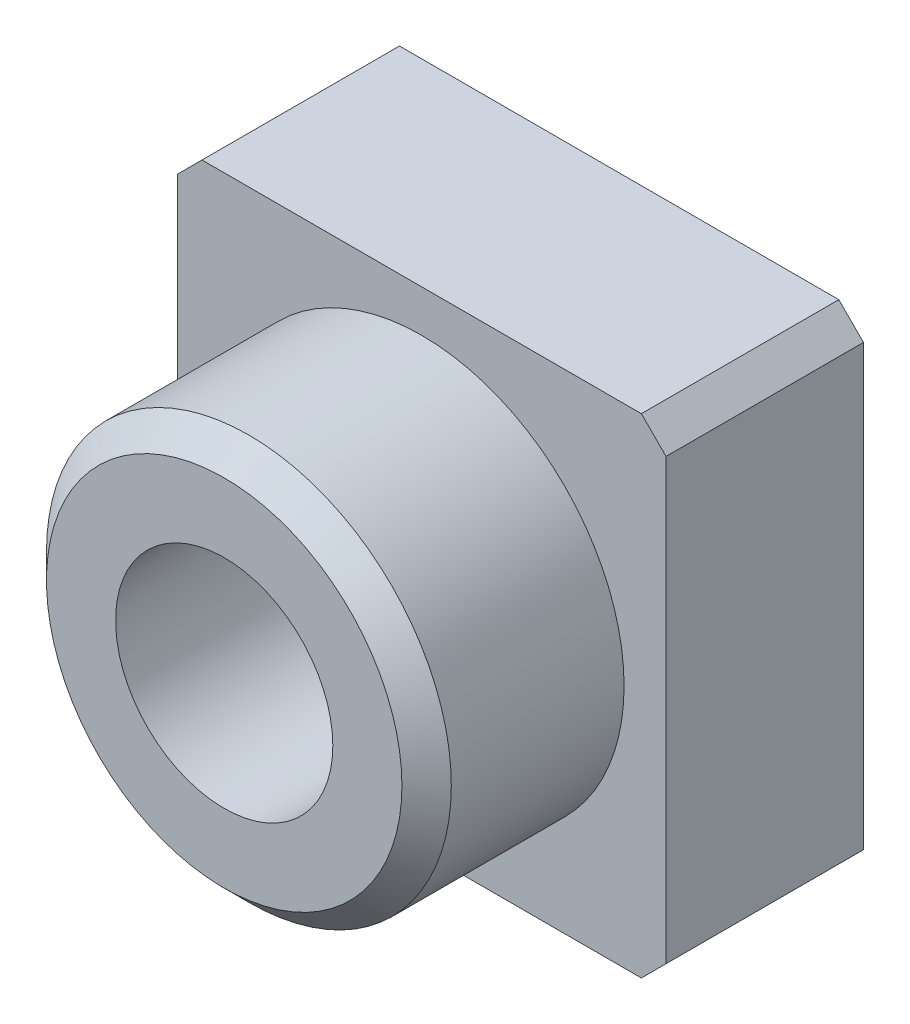
SolidWorks part; units mm, degrees
ref_plane "Plan de face" through (0, 0, 0) normal (0, 0, 1) x (1, 0, 0)
ref_plane "Plan de dessus" through (0, 0, 0) normal (0, 1, 0) x (1, 0, 0)
ref_plane "Plan de droite" through (0, 0, 0) normal (1, 0, 0) x (0, 0, -1)
sketch "Esquisse1" plane through (0, 0, 0) normal (0, 0, 1) x (1, 0, 0)
  line L1 (-4.95, -4.95) -> (4.95, -4.95)
  line L2 (-4.95, -4.95) -> (-4.95, 4.95)
  line L3 (-4.95, 4.95) -> (4.95, 4.95)
  line L4 (4.95, -4.95) -> (4.95, 4.95)
  line L5 (-4.95, -4.95) -> (4.95, 4.95) construction
  line L6 (-4.95, 4.95) -> (4.95, -4.95) construction
  point P0 (0, 0)
  dimension "D1" = 9.9
extrude "Boss.-Extru.1" add sketch "Esquisse1" along normal blind 4
sketch "Esquisse2" plane through (0, 0, 0) normal (0, 0, 1) x (1, 0, 0)
  line L1 (4.1569, 0) -> (2.0785, 3.6)
  line L2 (2.0785, 3.6) -> (-2.0785, 3.6)
  line L3 (-2.0785, 3.6) -> (-4.1569, 0)
  line L4 (-4.1569, 0) -> (-2.0785, -3.6)
  line L5 (-2.0785, -3.6) -> (2.0785, -3.6)
  line L6 (2.0785, -3.6) -> (4.1569, 0)
  circle A0 centre (0, 0) radius 3.6 construction
  dimension "D1" = 7.2
extrude "Enlèv. mat.-Extru.1" cut sketch "Esquisse2" along normal offset from surface (3.2 mm away) 0.8 up to face at (0, 0, 4)
sketch "Esquisse4" plane through (0, 0, 4) normal (0, 0, 1) x (1, 0, 0)
  circle A0 centre (0, 0) radius 4.1
  dimension "D1" = 8.2
extrude "Boss.-Extru.2" add sketch "Esquisse4" along normal blind 4
chamfer "Chanfrein1" distance 0.5 angle 45 1 edges at (4.1, 0, 8)
sketch "Esquisse5" plane through (0, 0, 8) normal (0, 0, 1) x (1, 0, 0)
  circle A0 centre (0, 0) radius 2.2
  dimension "D1" = 4.4
extrude "Enlèv. mat.-Extru.3" cut sketch "Esquisse5" against normal through all
chamfer "Chanfrein2" distance 0.5 angle 45 4 edges at (4.95, -4.95, 2) (4.95, 4.95, 2) (-4.95, -4.95, 2) (-4.95, 4.95, 2)
